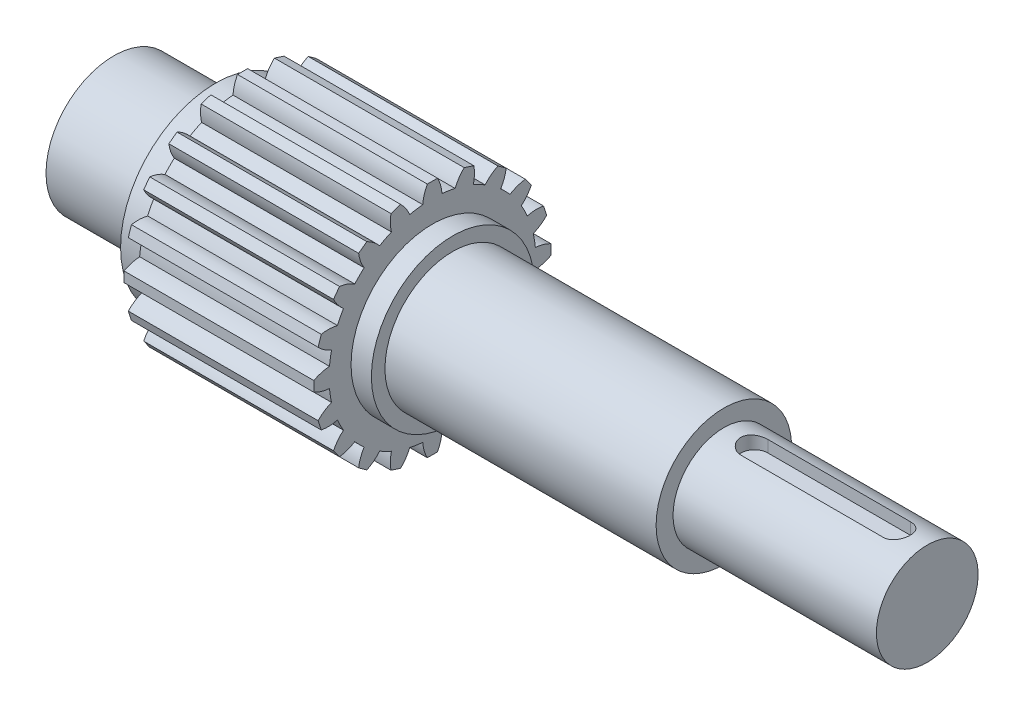
SolidWorks part; units mm, degrees
ref_plane "前视基准面" through (0, 0, 0) normal (0, 0, 1) x (1, 0, 0)
ref_plane "上视基准面" through (0, 0, 0) normal (0, 1, 0) x (1, 0, 0)
ref_plane "右视基准面" through (0, 0, 0) normal (1, 0, 0) x (0, 0, -1)
sketch "草图1" plane through (0, 0, 0) normal (0, 0, 1) x (1, 0, 0)
  line L0 (-87.9061, 0) -> (306.9405, 0) construction
  line L1 (-56.9279, 0) -> (183.0721, 0)
  line L2 (183.0721, 0) -> (183.0721, 15)
  line L3 (183.0721, 15) -> (123.0721, 15)
  line L4 (123.0721, 15) -> (123.0721, 20)
  line L5 (123.0721, 20) -> (43.0721, 20)
  line L6 (43.0721, 20) -> (43.0721, 24)
  line L7 (43.0721, 24) -> (-18.9279, 24)
  line L8 (-18.9279, 24) -> (-18.9279, 28)
  line L9 (-18.9279, 28) -> (-26.9279, 28)
  line L10 (-26.9279, 28) -> (-26.9279, 20)
  line L11 (-26.9279, 20) -> (-56.9279, 20)
  line L12 (-56.9279, 20) -> (-56.9279, 0)
  dimension "D1" = 15
  dimension "D2" = 5
  dimension "D3" = 4
  dimension "D4" = 4
  dimension "D5" = 8
  dimension "D6" = 62
  dimension "D7" = 80
  dimension "D8" = 60
revolve "旋转2" add sketch "草图1" angle 360 about L0
ref_plane "基准面1" through (0, 15, 0) normal (0, 1, 0) x (-1, 0, 0)
sketch "草图2" plane through (0, 15, 0) normal (0, 1, 0) x (-1, 0, 0)
  line L0 (-183.0721, 0) -> (-123.0721, 0) construction
  line L1 (-183.0721, 15) -> (-183.0721, -15) construction
  line L2 (-123.0721, 20) -> (-123.0721, -20) construction
  line L4 (-174.0721, -4) -> (-132.0721, -4)
  line L6 (-174.0721, 4) -> (-132.0721, 4)
  line L8 (-174.0721, -4) -> (-132.0721, 4) construction
  line L9 (-174.0721, 4) -> (-132.0721, -4) construction
  arc A0 (-174.0721, 4) -> (-174.0721, -4) centre (-174.0721, 0) ccw
  arc A1 (-132.0721, 4) -> (-132.0721, -4) centre (-132.0721, 0) cw
  point P6 (-153.0721, 0)
  dimension "D1" = 8
  dimension "D2" = 42
extrude "切除-拉伸1" cut sketch "草图2" against normal blind 4
sketch "草图3" plane through (0, 0, 0) normal (0, 0, 1) x (1, 0, 0)
  line L0 (-56.9279, 0) -> (183.0721, 0) construction
  line L1 (-56.9279, 20) -> (-56.9279, -20) construction
  line L2 (183.0721, -15) -> (183.0721, 15) construction
  line L4 (-18.9279, 24) -> (37.0721, 24)
  line L5 (-18.9279, 24) -> (-18.9279, 30.5)
  line L6 (-18.9279, 30.5) -> (37.0721, 30.5)
  line L7 (37.0721, 24) -> (37.0721, 30.5)
  dimension "D1" = 56
  dimension "D2" = 6.5
revolve "旋转4" add sketch "草图3" angle 360 about L0
sketch "草图5" plane through (37.0721, 0, 0) normal (1, 0, 0) x (0, 0, -1)
  line L0 (0, -38.3339) -> (0, 45.6613) construction
  line L1 (-2.6356, 27.3689) -> (2.6356, 27.3689)
  line L2 (-1.5, 35.8625) -> (-1.5, 33.9851) construction
  line L3 (-2.6356, 28.6789) -> (-2.6356, 26.059) construction
  line L4 (-1.5, 34.9678) -> (1.5, 34.9678)
  arc A2 (-1.5, 34.9678) -> (-2.6356, 27.3689) centre (8.4475, 29.5969) ccw
  arc A5 (1.5, 34.9678) -> (2.6356, 27.3689) centre (-8.4475, 29.5969) cw
  dimension "D1" = 7.5989
  dimension "D2" = 1.5
  dimension "D3" = 2.6356
extrude "凸台-拉伸1" add sketch "草图5" against normal blind 56
pattern_circular "阵列(圆周)1" count 20 over 360 about axis through (0, 0, 0) along (1, 0, 0) of "凸台-拉伸1"
